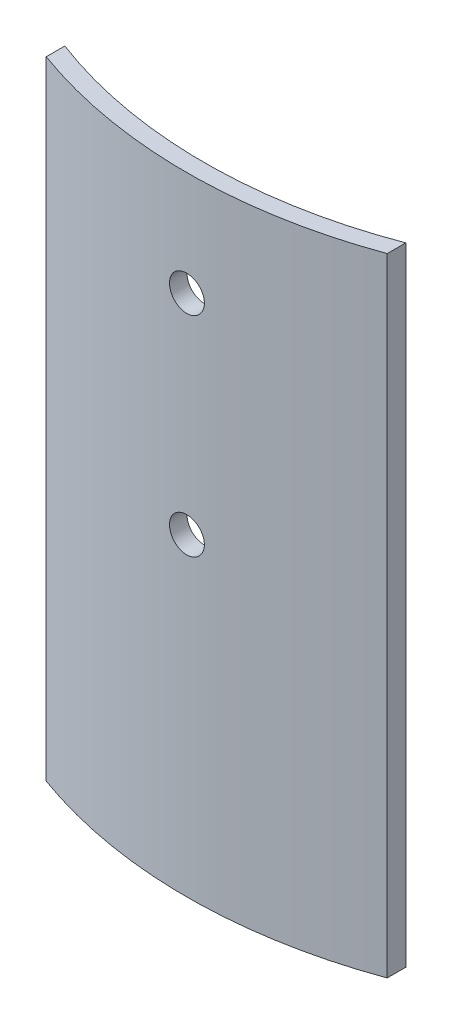
SolidWorks part; units mm, degrees
material "Thornel Mat VMA"
ref_plane "Front Plane" through (0, 0, 0) normal (0, 0, 1) x (1, 0, 0)
ref_plane "Top Plane" through (0, 0, 0) normal (0, 1, 0) x (1, 0, 0)
ref_plane "Right Plane" through (0, 0, 0) normal (1, 0, 0) x (0, 0, -1)
ref_plane "Plane1" through (0, 75, 0) normal (0, 1, 0) x (1, 0, 0)
sketch "Sketch1" plane through (0, 0, 0) normal (0, 1, 0) x (1, 0, 0)
  line L0 (0, 0) -> (0, -66.5) construction
  line L1 (66.5, 0) -> (-66.5, 0) construction
  line L2 (-55.8763, 32.2602) -> (-43.648, 53.4402)
  line L3 (0, 0) -> (57.5907, 33.25) construction
  line L4 (0, 0) -> (-57.5907, 33.25) construction
  line L5 (-43.648, 53.4402) -> (-68.1046, 11.0801)
  line L6 (-53.3763, 36.5903) -> (-58.3763, 27.93)
  line L7 (-58.3763, 27.93) -> (-40.7703, 17.7652)
  line L8 (0, -64.5203) -> (-24.4566, -64.5203)
  line L9 (-24.4566, -64.5203) -> (24.4566, -64.5203)
  line L10 (-40.7703, 17.7652) -> (-35.7703, 26.4255)
  line L11 (-58.3763, 27.93) -> (-59.9277, 28.8258)
  line L12 (-53.3763, 36.5903) -> (-35.7703, 26.4255)
  line L13 (-50.8763, 40.9204) -> (-54.1249, 42.796)
  line L14 (-60.8763, 23.5999) -> (-64.1249, 25.4755)
  line L15 (-50.8763, 40.9204) -> (-28.9402, 28.2556) construction
  line L16 (-38.9402, 10.9351) -> (-28.9402, 28.2556) construction
  line L17 (-60.8763, 23.5999) -> (-38.9402, 10.9351) construction
  line L18 (55.8763, 32.2602) -> (68.1046, 11.0801)
  line L19 (68.1046, 11.0801) -> (43.648, 53.4402)
  line L20 (58.3763, 27.93) -> (53.3763, 36.5903)
  line L21 (53.3763, 36.5903) -> (35.7703, 26.4255)
  line L22 (35.7703, 26.4255) -> (40.7703, 17.7652)
  line L23 (53.3763, 36.5903) -> (54.9277, 37.486)
  line L24 (58.3763, 27.93) -> (40.7703, 17.7652)
  line L25 (60.8763, 23.5999) -> (64.1249, 25.4755)
  line L26 (-5, -64.5203) -> (5, -64.5203)
  line L27 (5, -64.5203) -> (5, -44.1907)
  line L28 (5, -44.1907) -> (-5, -44.1907)
  line L29 (5, -64.5203) -> (5, -66.3118)
  line L30 (-5, -64.5203) -> (-5, -44.1907)
  line L32 (50.8763, 40.9204) -> (54.1249, 42.796)
  line L33 (60.8763, 23.5999) -> (38.9402, 10.9351) construction
  line L34 (28.9402, 28.2556) -> (38.9402, 10.9351) construction
  line L35 (50.8763, 40.9204) -> (28.9402, 28.2556) construction
  line L36 (-24.4566, -64.5203) -> (-24.4566, -67.1872)
  line L37 (24.4566, -64.5203) -> (24.4566, -67.1872)
  line L58 (-10, -64.5203) -> (-10, -39.1907) construction
  line L59 (10, -39.1907) -> (-10, -39.1907) construction
  line L60 (10, -64.5203) -> (10, -39.1907) construction
  line L61 (-10, -64.5203) -> (-10, -68.2715)
  line L62 (10, -64.5203) -> (10, -68.2715)
  line L63 (10, -64.5203) -> (10, -66.3118) construction
  circle A0 centre (0, 0) radius 66.5
  circle A1 centre (0, 0) radius 69
  circle A2 centre (0, 0) radius 71.5
  circle A4 centre (0, 0) radius 3.975
  circle A5 centre (0, 0) radius 11.1125
  point P14 (0, 0)
  point P26 (-38.2703, 22.0954)
  point P39 (0, -44.1907)
  point P51 (38.2703, 22.0954)
  point P58 (0, 0)
  point P67 (0, 0)
  point P68 (0, 0)
  point P71 (0, 0)
  point P81 (0, 0)
  dimension "D1" = 133
  dimension "D2" = 138
  dimension "D3" = 50
  dimension "D5" = 30
  dimension "D11" = 7.95
  dimension "D12" = 22.225
  dimension "D8" = 3
  dimension "D9" = 5
  dimension "D10" = 22.3093
  dimension "D4" = 30
  dimension "D7" = 5
  dimension "D6" = 5
sketch "Sketch16" plane through (0, 75, 0) normal (0, -1, 0) x (1, 0, 0)
  line L0 (-24.4566, 64.5203) -> (24.4566, 64.5203)
  line L1 (-5, 64.5203) -> (-5, 44.1907)
  line L2 (-5, 44.1907) -> (5, 44.1907)
  line L3 (5, 44.1907) -> (5, 66.3118)
  line L4 (0, 66.5) -> (0, 0) construction
  line L5 (-66.5, 0) -> (66.5, 0) construction
  line L14 (0, 0) -> (57.5907, -33.25) construction
  line L15 (0, 0) -> (-57.5907, -33.25) construction
  line L16 (-10, 64.5203) -> (-10, 39.1907) construction
  line L17 (-10, 39.1907) -> (10, 39.1907) construction
  line L18 (10, 39.1907) -> (10, 68.2715) construction
  line L19 (-68.1046, -11.0801) -> (-43.648, -53.4402)
  line L20 (-43.648, -53.4402) -> (-53.3763, -36.5903)
  line L21 (-53.3763, -36.5903) -> (-35.7703, -26.4255)
  line L22 (-35.7703, -26.4255) -> (-40.7703, -17.7652)
  line L23 (-40.7703, -17.7652) -> (-59.9277, -28.8258)
  line L25 (5, 44.1907) -> (5, 65.7874) construction
  line L27 (10, 39.1907) -> (10, 65.7874) construction
  line L28 (-64.1249, -25.4755) -> (-38.9402, -10.9351) construction
  line L29 (-38.9402, -10.9351) -> (-28.9402, -28.2556) construction
  line L30 (-28.9402, -28.2556) -> (-54.1249, -42.796) construction
  line L31 (43.648, -53.4402) -> (68.1046, -11.0801)
  line L32 (54.9277, -37.486) -> (35.7703, -26.4255)
  line L33 (35.7703, -26.4255) -> (40.7703, -17.7652)
  line L34 (40.7703, -17.7652) -> (58.3763, -27.93)
  line L38 (54.1249, -42.796) -> (28.9402, -28.2556) construction
  line L39 (28.9402, -28.2556) -> (38.9402, -10.9351) construction
  line L40 (38.9402, -10.9351) -> (64.1249, -25.4755) construction
  circle A2 centre (0, 0) radius 68.75
  circle A3 centre (0, 0) radius 67.5
  dimension "D1" = 137.5
  dimension "D2" = 135
  dimension "D3" = 5
extrude "Boss-Extrude9" add sketch "Sketch1" along normal blind 90 contours L36 A2 L37 A1
ref_plane "Plane2" through (0, 0, 67.1872) normal (0, 0, 1) x (1, 0, 0)
sketch "Sketch17" plane through (0, 0, 67.1872) normal (0, 0, 1) x (1, 0, 0)
  line L0 (0, 90) -> (0, 0)
  line L1 (-24.4566, 90) -> (24.4566, 90)
  line L2 (-24.4566, 90) -> (-24.4566, 26.9653)
  line L3 (-24.4566, 26.9653) -> (24.4566, 26.9653)
  line L4 (24.4566, 90) -> (24.4566, 26.9653)
  line L5 (0, 0) -> (0, 45)
  line L6 (0, 45) -> (0, 75)
  circle A0 centre (0, 75) radius 2.5
  circle A1 centre (0, 45) radius 2.5
  dimension "D3" = 5
  dimension "D1" = 15
  dimension "D2" = 30
extrude "Cut-Extrude1" cut sketch "Sketch17" against normal mid plane 10 contours A0 | A1
